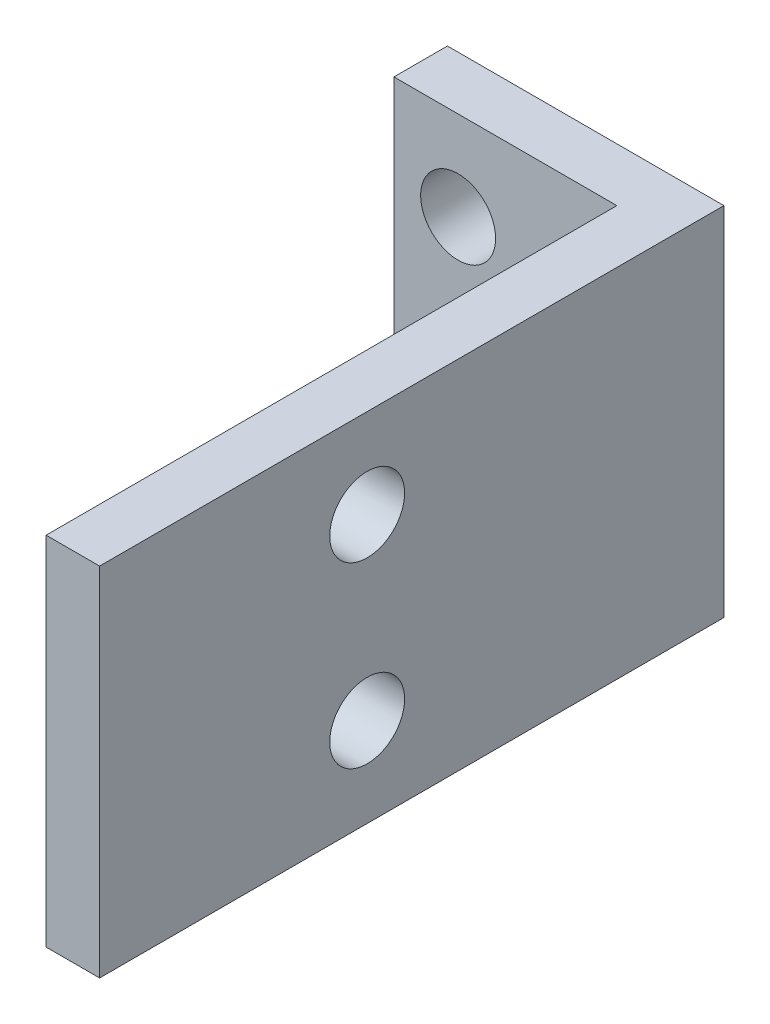
SolidWorks part; units mm, degrees
ref_plane "前视基准面" through (0, 0, 0) normal (0, 0, 1) x (1, 0, 0)
ref_plane "上视基准面" through (0, 0, 0) normal (0, 1, 0) x (1, 0, 0)
ref_plane "右视基准面" through (0, 0, 0) normal (1, 0, 0) x (0, 0, -1)
ref_plane "基准面4" through (20.5, 0, 0) normal (-1, 0, 0) x (0, -1, 0)
sketch "草图1" plane through (20.5, 0, 0) normal (-1, 0, 0) x (0, -1, 0)
  line L0 (50, -10) -> (50, 25)
  line L1 (50, 25) -> (30, 25)
  line L2 (30, 25) -> (30, -10)
  line L3 (30, -10) -> (50, -10)
extrude "凸台-拉伸1" add sketch "草图1" against normal blind 15.5
sketch "草图2" plane through (0, -50, 0) normal (0, -1, 0) x (1, 0, 0)
  line L0 (20.5, -7) -> (33, -7)
  line L1 (33, -7) -> (33, 25)
  line L2 (33, 25) -> (20.5, 25)
  line L3 (20.5, 25) -> (20.5, -7)
extrude "切除-拉伸1" cut sketch "草图2" against normal through all
hole_wizard "Ø4.2 (4.2) 直径孔1" positions "草图4" profile "草图3" hole size "Ø4.2" standard "ANSI Metric"
sketch "草图4" plane through (36, 0, 0) normal (1, 0, 0) x (0, 0, -1)
  point P0 (-10, -35)
  point P1 (-10, -45)
sketch "草图3" plane through (36, -35, 10) normal (0, 1, 0) x (0, 0, -1)
  line L0 (0, 0) -> (0, 15.5)
  line L1 (0, 15.5) -> (2.1, 15.5)
  line L2 (2.1, 15.5) -> (2.1, 0)
  line L5 (2.1, 0) -> (0, 0)
  line L11 (0, -6.35) -> (0, 107.95) construction
  dimension "通孔孔直径" = 4.2
  dimension "通孔孔深度" = 15.5
hole_wizard "Ø4.2 (4.2) 直径孔2" positions "草图6" profile "草图5" hole size "Ø4.2" standard "ANSI Metric"
sketch "草图6" plane through (0, 0, -7) normal (0, 0, 1) x (1, 0, 0)
  point P0 (24.1, -45)
  point P1 (24.1, -35)
sketch "草图5" plane through (24.1, -45, -7) normal (1, 0, 0) x (0, -1, 0)
  line L0 (0, 0) -> (0, 3)
  line L1 (0, 3) -> (2.1, 3)
  line L2 (2.1, 3) -> (2.1, 0)
  line L5 (2.1, 0) -> (0, 0)
  line L11 (0, -6.35) -> (0, 107.95) construction
  dimension "通孔孔直径" = 4.2
  dimension "通孔孔深度" = 3
